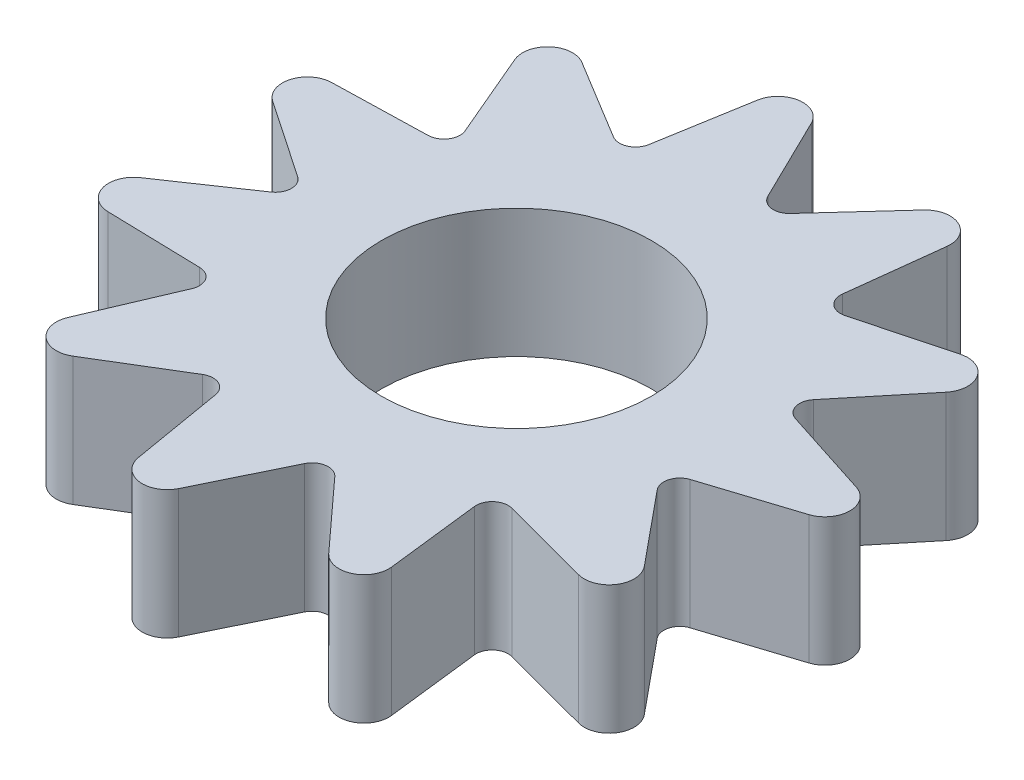
SolidWorks part; units mm, degrees
ref_plane "Front Plane" through (0, 0, 0) normal (0, 0, 1) x (1, 0, 0)
ref_plane "Top Plane" through (0, 0, 0) normal (0, 1, 0) x (1, 0, 0)
ref_plane "Right Plane" through (0, 0, 0) normal (1, 0, 0) x (0, 0, -1)
sketch "Sketch1" plane through (0, 0, 0) normal (0, 1, 0) x (1, 0, 0)
  line L0 (-14.6509, 0) -> (23.5302, 0) construction
  line L1 (0, 0) -> (20.4458, 6.0034) construction
  line L2 (3.5229, 0.8189) -> (4.919, 0.3696)
  line L3 (3.5229, -0.8189) -> (4.919, -0.3696)
  line L4 (3.4064, -1.2157) -> (4.3379, -2.3484)
  line L5 (2.5209, -2.5935) -> (3.9383, -2.9703)
  line L6 (2.2084, -2.8643) -> (2.3796, -4.3209)
  line L7 (0.7185, -3.5447) -> (1.7072, -4.628)
  line L8 (0.3092, -3.6035) -> (-0.3342, -4.9215)
  line L9 (-1.3119, -3.3705) -> (-1.0659, -4.8163)
  line L10 (-1.6881, -3.1987) -> (-2.9419, -3.9595)
  line L11 (-2.9259, -2.1261) -> (-3.5006, -3.4754)
  line L12 (-3.1494, -1.7782) -> (-4.6156, -1.7405)
  line L13 (-3.6109, -0.2068) -> (-4.8238, -1.0312)
  line L14 (-3.6109, 0.2068) -> (-4.8238, 1.0312)
  line L15 (-3.1494, 1.7782) -> (-4.6156, 1.7405)
  line L16 (-2.9259, 2.1261) -> (-3.5006, 3.4754)
  line L17 (-1.6881, 3.1987) -> (-2.9419, 3.9595)
  line L18 (-1.3119, 3.3705) -> (-1.0659, 4.8163)
  line L19 (0.3092, 3.6035) -> (-0.3342, 4.9215)
  line L20 (0.7185, 3.5447) -> (1.7072, 4.628)
  line L21 (2.2084, 2.8643) -> (2.3796, 4.3209)
  line L22 (2.5209, 2.5935) -> (3.9383, 2.9703)
  line L23 (3.4064, 1.2157) -> (4.3379, 2.3484)
  circle A0 centre (0, 0) radius 2.1
  circle A1 centre (0, 0) radius 3.5014
  circle A2 centre (0, 0) radius 5.5014 construction
  arc A3 (3.3596, 0.9865) -> (3.5229, 0.8189) centre (3.5995, 1.0569) ccw
  arc A5 (3.3596, -0.9865) -> (3.5229, -0.8189) centre (3.5995, -1.0569) cw
  arc A6 (3.3596, -0.9865) -> (3.4064, -1.2157) centre (3.5995, -1.0569) ccw
  arc A8 (2.2929, -2.6462) -> (2.5209, -2.5935) centre (2.4567, -2.8351) cw
  arc A9 (2.2929, -2.6462) -> (2.2084, -2.8643) centre (2.4567, -2.8351) ccw
  arc A11 (0.4983, -3.4658) -> (0.7185, -3.5447) centre (0.5339, -3.7132) cw
  arc A12 (0.4983, -3.4658) -> (0.3092, -3.6035) centre (0.5339, -3.7132) ccw
  arc A14 (-1.4545, -3.185) -> (-1.3119, -3.3705) centre (-1.5584, -3.4124) cw
  arc A15 (-1.4545, -3.185) -> (-1.6881, -3.1987) centre (-1.5584, -3.4124) ccw
  arc A17 (-2.9456, -1.893) -> (-2.9259, -2.1261) centre (-3.1559, -2.0282) cw
  arc A18 (-2.9456, -1.893) -> (-3.1494, -1.7782) centre (-3.1559, -2.0282) ccw
  arc A20 (-3.5014, 0) -> (-3.6109, -0.2068) centre (-3.7514, 0) cw
  arc A21 (-3.5014, 0) -> (-3.6109, 0.2068) centre (-3.7514, 0) ccw
  arc A23 (-2.9456, 1.893) -> (-3.1494, 1.7782) centre (-3.1559, 2.0282) cw
  arc A24 (-2.9456, 1.893) -> (-2.9259, 2.1261) centre (-3.1559, 2.0282) ccw
  arc A26 (-1.4545, 3.185) -> (-1.6881, 3.1987) centre (-1.5584, 3.4124) cw
  arc A27 (-1.4545, 3.185) -> (-1.3119, 3.3705) centre (-1.5584, 3.4124) ccw
  arc A29 (0.4983, 3.4658) -> (0.3092, 3.6035) centre (0.5339, 3.7132) cw
  arc A30 (0.4983, 3.4658) -> (0.7185, 3.5447) centre (0.5339, 3.7132) ccw
  arc A32 (2.2929, 2.6462) -> (2.2084, 2.8643) centre (2.4567, 2.8351) cw
  arc A33 (2.2929, 2.6462) -> (2.5209, 2.5935) centre (2.4567, 2.8351) ccw
  arc A35 (3.3596, 0.9865) -> (3.4064, 1.2157) centre (3.5995, 1.0569) cw
  arc A36 (4.919, -0.3696) -> (4.919, 0.3696) centre (4.8, 0) ccw
  arc A37 (3.9383, -2.9703) -> (4.3379, -2.3484) centre (4.038, -2.5951) ccw
  arc A38 (1.7072, -4.628) -> (2.3796, -4.3209) centre (1.994, -4.3662) ccw
  arc A39 (-1.0659, -4.8163) -> (-0.3342, -4.9215) centre (-0.6831, -4.7511) ccw
  arc A40 (-3.5006, -3.4754) -> (-2.9419, -3.9595) centre (-3.1433, -3.6276) ccw
  arc A41 (-4.8238, -1.0312) -> (-4.6156, -1.7405) centre (-4.6056, -1.3523) ccw
  arc A42 (-4.6156, 1.7405) -> (-4.8238, 1.0312) centre (-4.6056, 1.3523) ccw
  arc A43 (-2.9419, 3.9595) -> (-3.5006, 3.4754) centre (-3.1433, 3.6276) ccw
  arc A44 (-0.3342, 4.9215) -> (-1.0659, 4.8163) centre (-0.6831, 4.7511) ccw
  arc A45 (2.3796, 4.3209) -> (1.7072, 4.628) centre (1.994, 4.3662) ccw
  arc A46 (4.3379, 2.3484) -> (3.9383, 2.9703) centre (4.038, 2.5951) ccw
  point P109 (0, 0)
  point P132 (0, 0)
  dimension "D1" = 4.2
  dimension "D2" = 7.0028
  dimension "D3" = 2
  dimension "D5" = 0.5
  dimension "D4" = 16.364
  dimension "D8" = 4.8
  dimension "D7" = 11
  dimension "D9" = 11
extrude "Boss-Extrude3" add sketch "Sketch1" along normal blind 2 contours L15 A42 L14 A21 A1 A23 | L17 A43 L16 A24 A1 A26 | L19 A44 L18 A27 A1 A29 | L21 A45 L20 A30 A1 A32 | L23 A46 L22 A33 A1 A35 | L3 A36 L2 A3 A1 A5 | L5 A37 L4 A6 A1 A8 | L7 A38 L6 A9 A1 A11 | L9 A39 L8 A12 A1 A14 | L11 A40 L10 A15 A1 A17 | L13 A41 L12 A18 A1 A20 | A1 A0
